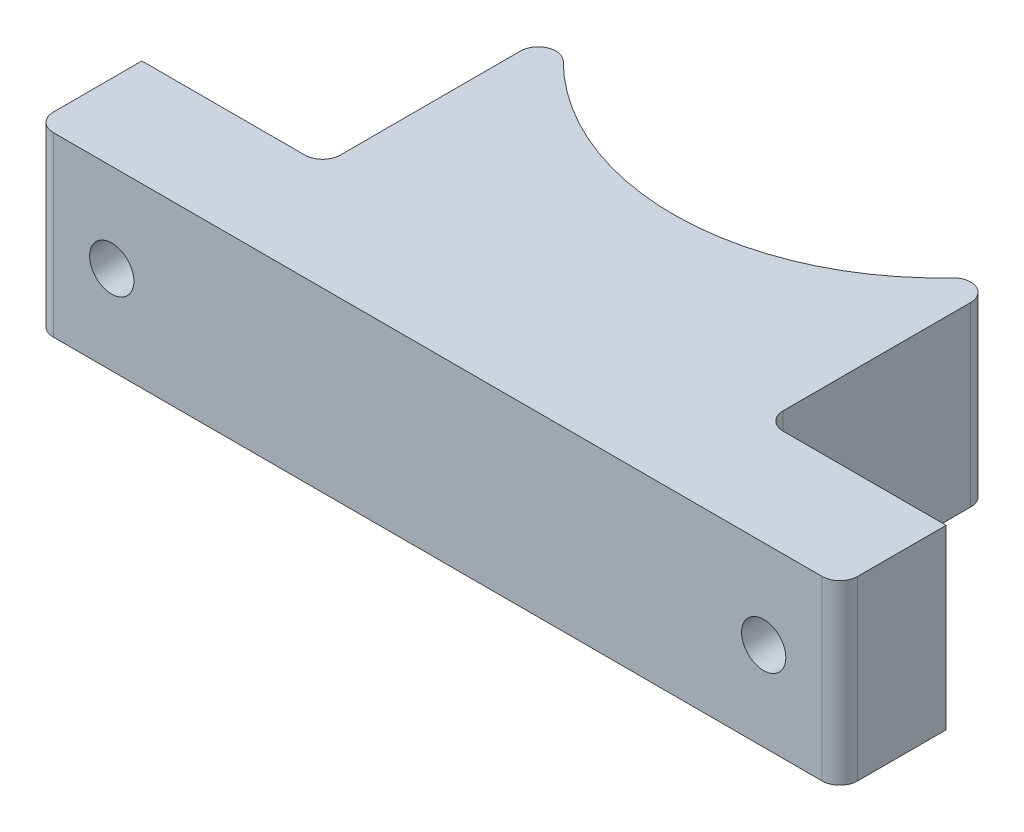
SolidWorks part; units mm, degrees
ref_plane "Front Plane" through (0, 0, 0) normal (0, 0, 1) x (1, 0, 0)
ref_plane "Top Plane" through (0, 0, 0) normal (0, 1, 0) x (1, 0, 0)
ref_plane "Right Plane" through (0, 0, 0) normal (1, 0, 0) x (0, 0, -1)
sketch "Sketch2" plane through (0, 0, 0) normal (0, 1, 0) x (1, 0, 0)
  line L0 (-24.6, 28.3452) -> (-24.6, 8)
  line L1 (-45, 6) -> (-26.6, 6)
  line L2 (-45, 6) -> (-45, -4)
  line L3 (-43, -6) -> (43.8, -6)
  line L4 (45.8, 6) -> (45.8, -4)
  line L5 (25.4, 8) -> (25.4, 29.1725)
  line L6 (27.4, 6) -> (45.8, 6)
  arc A0 (-21.1875, 29.7611) -> (21.9375, 30.5367) centre (0, 51) ccw
  arc A1 (-24.6, 28.3452) -> (-21.1875, 29.7611) centre (-22.6, 28.3452) cw
  arc A2 (25.4, 29.1725) -> (21.9375, 30.5367) centre (23.4, 29.1725) ccw
  arc A3 (-24.6, 8) -> (-26.6, 6) centre (-26.6, 8) cw
  arc A4 (27.4, 6) -> (25.4, 8) centre (27.4, 8) cw
  arc A5 (-43, -6) -> (-45, -4) centre (-43, -4) cw
  arc A6 (45.8, -4) -> (43.8, -6) centre (43.8, -4) cw
  point P6 (0, 56)
  point P7 (0, 56)
  point P10 (-24.6, 33.8291)
  point P11 (0, 0)
  point P12 (25.4, 35.0363)
  point P15 (-45, 1)
  point P24 (25.4, 6)
  point P27 (-45, -6)
  point P30 (45.8, -6)
  dimension "D4" = 45
  dimension "D8" = 2
  dimension "D9" = 2
  dimension "D10" = 2
  dimension "D11" = 2
  dimension "D12" = 2
  dimension "D13" = 2
  dimension "D1" = 90.8
  dimension "D2" = 12
  dimension "D3" = 20.4
  dimension "D5" = 45
  dimension "D6" = 6
  dimension "D7" = 50
extrude "Boss-Extrude1" add sketch "Sketch2" along normal blind 20
sketch "Sketch3" plane through (0, 0, 6) normal (0, 0, 1) x (1, 0, 0)
  line L0 (-45, 20) -> (-45, 0) construction
  line L1 (-43, 0) -> (43.8, 0) construction
  line L2 (45.8, 20) -> (45.8, 0) construction
  circle A0 centre (-36.4, 10) radius 2.5
  circle A1 centre (37.2, 10) radius 2.5
  dimension "D1" = 8.6
  dimension "D3" = 10
  dimension "D2" = 10
  dimension "D4" = 8.6
extrude "Cut-Extrude1" cut sketch "Sketch3" against normal up to next
